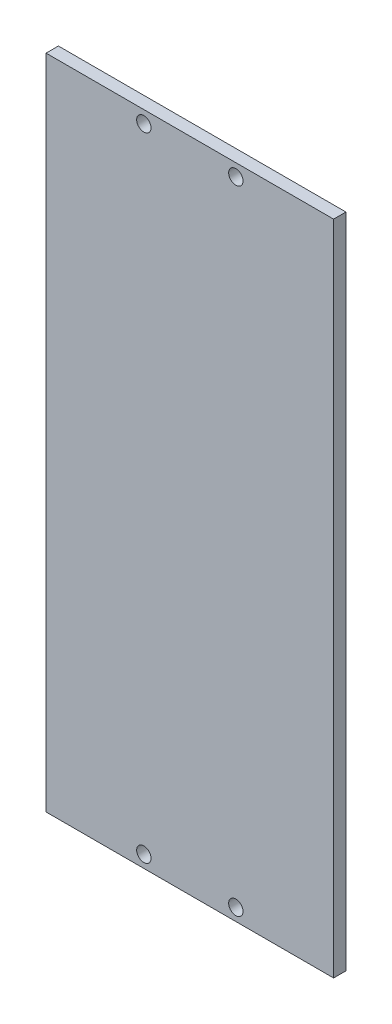
SolidWorks part; units mm, degrees
ref_plane "정면" through (0, 0, 0) normal (0, 0, 1) x (1, 0, 0)
ref_plane "윗면" through (0, 0, 0) normal (0, 1, 0) x (1, 0, 0)
ref_plane "우측면" through (0, 0, 0) normal (1, 0, 0) x (0, 0, -1)
sketch "스케치1" plane through (0, 0, 0) normal (0, 0, 1) x (1, 0, 0)
  line L8 (0, -106.8488) -> (0, 119.8748) construction
  line L17 (-11.2, 102.8748) -> (-11.2, -80) construction
  line L18 (35, -80) -> (-35, -80)
  line L19 (35, -80) -> (35, 80)
  line L20 (35, 80) -> (-35, 80)
  line L21 (-35, -80) -> (-35, 80)
  line L22 (35, -80) -> (-35, 80) construction
  line L23 (35, 80) -> (-35, -80) construction
  line L24 (-35, 0) -> (35, 0) construction
  line L25 (11.2, 102.8748) -> (11.2, -80) construction
  circle A8 centre (-11.2, 77) radius 1.75
  circle A9 centre (11.2, 77) radius 1.75
  circle A10 centre (11.2, -77) radius 1.75
  circle A11 centre (-11.2, -77) radius 1.75
  point P37 (0, 0)
  point P44 (-11.2, 77)
  point P45 (11.2, 77)
  dimension "D12" = 70
  dimension "D13" = 160
  dimension "D14" = 3
  dimension "D15" = 3
extrude "보스-돌출2" add sketch "스케치1" along normal blind 3
